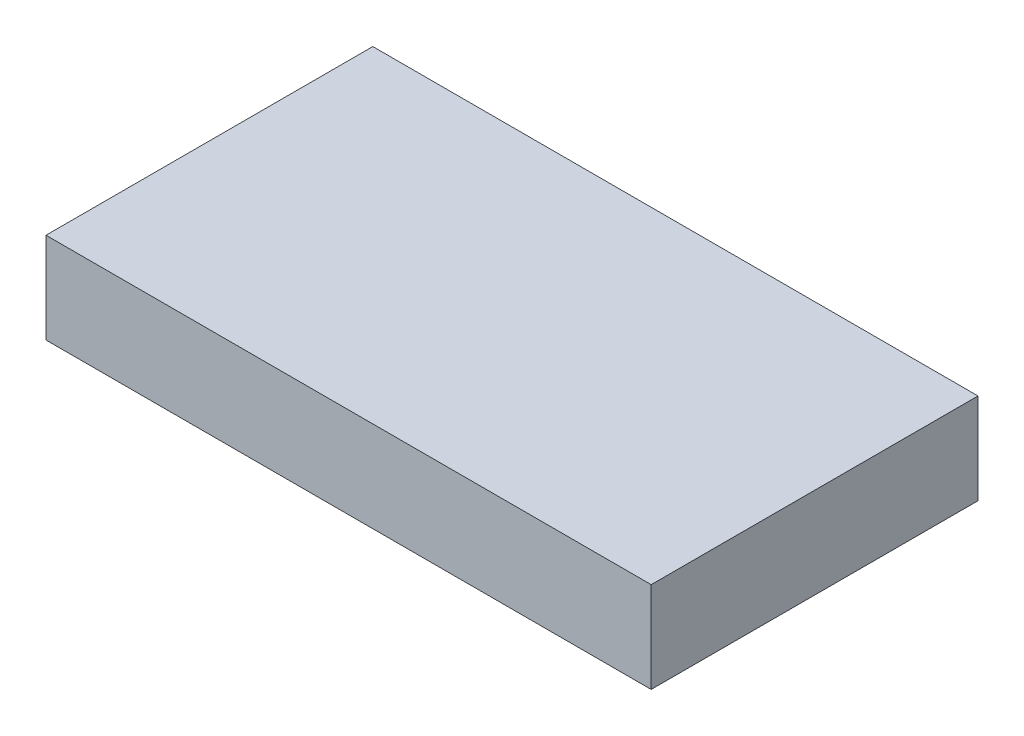
SolidWorks part; units mm, degrees
ref_plane "Front Plane" through (0, 0, 0) normal (0, 0, 1) x (1, 0, 0)
ref_plane "Top Plane" through (0, 0, 0) normal (0, 1, 0) x (1, 0, 0)
ref_plane "Right Plane" through (0, 0, 0) normal (1, 0, 0) x (0, 0, -1)
sketch "Sketch1" plane through (0, 0, 0) normal (0, 1, 0) x (1, 0, 0)
  line L1 (-152.2875, 62.9945) -> (-25.2875, 62.9945)
  line L2 (-152.2875, 62.9945) -> (-152.2875, -5.5855)
  line L3 (-152.2875, -5.5855) -> (-25.2875, -5.5855)
  line L4 (-25.2875, 62.9945) -> (-25.2875, -5.5855)
  dimension "D1" = 127
  dimension "D2" = 68.58
extrude "Boss-Extrude1" add sketch "Sketch1" along normal blind 19.05
